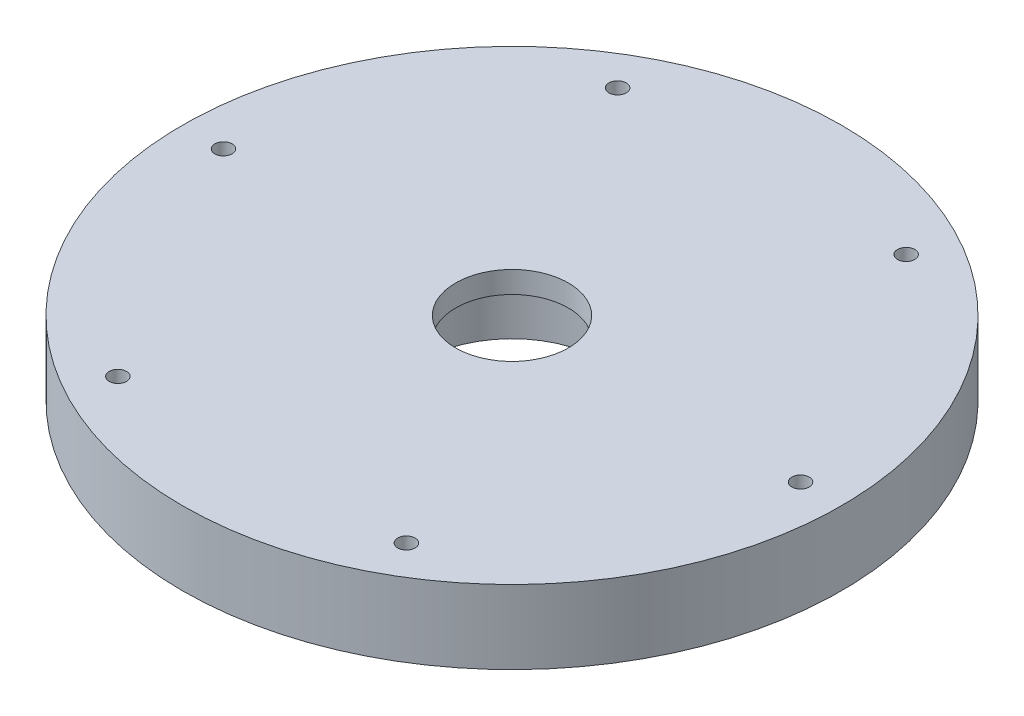
SolidWorks part; units mm, degrees
material "1060 Alloy"
ref_plane "Front Plane" through (0, 0, 0) normal (0, 0, 1) x (1, 0, 0)
ref_plane "Top Plane" through (0, 0, 0) normal (0, 1, 0) x (1, 0, 0)
ref_plane "Right Plane" through (0, 0, 0) normal (1, 0, 0) x (0, 0, -1)
sketch "Sketch1" plane through (0, 0, 0) normal (0, 0, 1) x (1, 0, 0)
  line L0 (0, 38.7087) -> (0, -19.5852) construction
  line L1 (-6.5, 0) -> (-38, 0)
  line L2 (-38, 0) -> (-38, -8.5)
  line L4 (-10.5, -9.75) -> (-10.5, -2.5)
  line L5 (-10.5, -2.5) -> (-6.5, -2.5)
  line L6 (-6.5, -2.5) -> (-6.5, 0)
  line L7 (-10.5, -9.75) -> (-35, -9.75)
  line L8 (-35, -9.75) -> (-35, -8.5)
  line L9 (-35, -8.5) -> (-38, -8.5)
  dimension "D1" = 6.5
  dimension "D2" = 10.5
  dimension "D4" = 38
  dimension "D5" = 3
  dimension "D6" = 1.25
  dimension "D7" = 2.5
  dimension "D3" = 6
revolve "Revolve1" add sketch "Sketch1" angle 360 about L0
sketch "Sketch2" plane through (0, -9.75, 0) normal (0, -1, 0) x (1, 0, 0)
  circle A0 centre (0, 0) radius 33.2687 construction
  circle A1 centre (-33.2687, 0) radius 1
  circle A2 centre (-16.6344, 28.8116) radius 1
  circle A3 centre (16.6344, 28.8116) radius 1
  circle A4 centre (33.2687, 0) radius 1
  circle A5 centre (16.6344, -28.8116) radius 1
  circle A6 centre (-16.6344, -28.8116) radius 1
  point P17 (0, 0)
  dimension "D1" = 2
  dimension "D3" = 66.5375
  dimension "D2" = 6
extrude "Cut-Extrude1" cut sketch "Sketch2" against normal through all
equation "\"Stator_OD\"= 60'No Tolerance given"
equation "\"A\"=35.81 'taken off spec sheet for 06808 (A)"
equation "\"Rotor_ID\"= 30'No Tolerance Given"
equation "\"back_bearing_Thickness\"= 5'-0.12"
equation "\"back_bearing_OD\"= 24'-0.009 https://www.mcmaster.com/5972K155/"
equation "\"Stator_Gap\"= 0.0375'+- 0.0125 (From 1.3.3.1 Kollmorgen manual)"
equation "\"Back_mount_hole\"= 1.75'To be tapped to M2 (USE LOCKTITE)"
equation "\"facePlate_Mount_Hole\"= 2.75'To be tapped to M3"
equation "\"back_bearing_ID\"= 15'"
equation "\"final_shaftD\"= 12'To fit in harmonic"
equation "\"final_shaftL\"= 5.25+3+\"sheet_thick\"+\"connector_thick\"-3+\"harmon_coupleL\"+0.5-\"shaft_Ladjust\"'length to make everything nice and aligned"
equation "\"back_bearing_IDOD\"= 16.5'measured off CAD, actually 16.75, but rounded down to nicer number"
equation "\"rotor_shaftD\"= \"Rotor_ID\" - (\"rotor-shaft_gap\")*2'"
equation "\"front_bearing_ID\"= 12'https://www.mcmaster.com/5972K154/"
equation "\"front_bearing_OD\"= 21'-0.009"
equation "\"front_bearing_IDOD\"= 13.5'Measured off CAD. Actually 13.75, but rounded down"
equation "\"front_bearing_Thickness\"= 5'-0.12"
equation "\"rotor_thickness\"= 2.4'measured off CAD"
equation "\"rotor_height\"= 32.86'+-0.075 taken off spec sheet for 06826 (C)"
equation "\"D1@Sketch1\"=\"final_shaftD\"/2+0.5"
equation "\"D2@Sketch1\"=\"front_bearing_OD\"/2"
equation "\"D4@Sketch1\"=\"Stator_OD\"/2+8"
equation "\"D3@Sketch1\"=\"front_bearing_Thickness\"+1"
equation "\"D3@Sketch2\"=\"Stator_OD\" + \"Stator_Gap\"  + 6.5"
equation "\"D1@Sketch2\"=\"Back_mount_hole\"+0.25"
equation "\"rotor-shaft_gap\" = 0.0185 '+-0.0065 (from manual)"
equation "\"B\"= 26.3'+-0.35 taken off spec sheet for 06826"
equation "\"key_L\"= 20'-0.2 https://www.mcmaster.com/2977N19/"
equation "\"key_H\"= 4'-0.03"
equation "\"key_W\"= 4'-0.03"
equation "\"harmon_keyH\"= 13.8'+0.1 from drawing"
equation "\"harmon_coupleL\"= 21.5' taken from drawing https://www.harmonicdrive.net/_hd/content/caddownloads/dxf/csf-2uh-ulw_gearheads/CSF-17-xxx-2UH-ULW.pdf"
equation "\"harmon_diam\"= 81' from drawing"
equation "\"harmon_BCD\"= 74.5' from drawing"
equation "\"harmon_holeD1\"= 3.4' from drawing"
equation "\"harmon_holeD2\"= 3' from drawing"
equation "\"harmon_holeAng\"= 18' from drawing"
equation "\"sheet_thick\"= 1/8*25.4 'random, replace w actual sheet thickness when u feel like :)"
equation "\"nut-thickness\"= 5 'idk measure the ones in the shop and adjust"
equation "\"connector_thick\"= 10' random for now"
equation "\"shaft_Ladjust\"= 6.75' sorry. It's silly, but it works."
